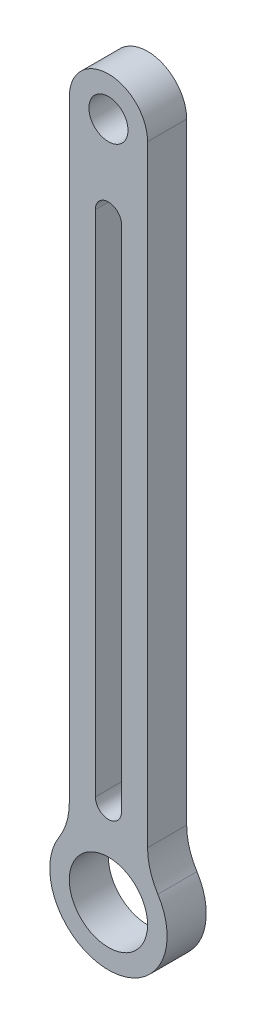
SolidWorks part; units mm, degrees
material "Thornel Mat VMA"
ref_plane "前视基准面" through (0, 0, 0) normal (0, 0, 1) x (1, 0, 0)
ref_plane "上视基准面" through (0, 0, 0) normal (0, 1, 0) x (1, 0, 0)
ref_plane "右视基准面" through (0, 0, 0) normal (1, 0, 0) x (0, 0, -1)
other "Configuration Table"
sketch "草图1" plane through (0, 0, 0) normal (0, 0, 1) x (1, 0, 0)
  line L0 (0, -52) -> (0, 52) construction
  line L1 (-6, -52) -> (-6, 52)
  line L2 (6, -52) -> (6, 52)
  arc A0 (-6, -52) -> (6, -52) centre (0, -52) ccw
  arc A1 (6, 52) -> (-6, 52) centre (0, 52) ccw
  point P2 (0, 0)
  dimension "D1" = 104
  dimension "D2" = 12
extrude "凸台-拉伸1" add sketch "草图1" along normal blind 6
sketch "草图2" plane through (0, 0, 0) normal (0, 0, -1) x (-1, 0, 0)
  circle A0 centre (0, -52) radius 9
  dimension "D1" = 18
extrude "凸台-拉伸2" add sketch "草图2" against normal up to surface (6 mm away) up to face at (0, 0, 6)
sketch "草图3" plane through (0, 0, 0) normal (0, 0, -1) x (-1, 0, 0)
  circle A0 centre (0, -52) radius 6
  circle A1 centre (0, 52) radius 3
  dimension "D1" = 6
  dimension "D2" = 12
extrude "切除-拉伸1" cut sketch "草图3" against normal up to surface (6 mm away) up to face at (0, 0.9271, 6)
fillet "圆角1" radius 10 2 edges at (-6, -45.2918, 3) (6, -45.2918, 3)
sketch "草图4" plane through (0, 0, 6) normal (0, 0, 1) x (1, 0, 0)
  line L0 (0, -39) -> (0, 39) construction
  line L1 (-2, -39) -> (-2, 39)
  line L2 (2, -39) -> (2, 39)
  arc A0 (-2, -39) -> (2, -39) centre (0, -39) ccw
  arc A1 (2, 39) -> (-2, 39) centre (0, 39) ccw
  circle A2 centre (0, 52) radius 3 construction
  point P2 (0, 0)
  dimension "D1" = 4
  dimension "D2" = 13
extrude "切除-拉伸2" cut sketch "草图4" against normal up to surface (6 mm away) up to face at (-6, -52, 0)
